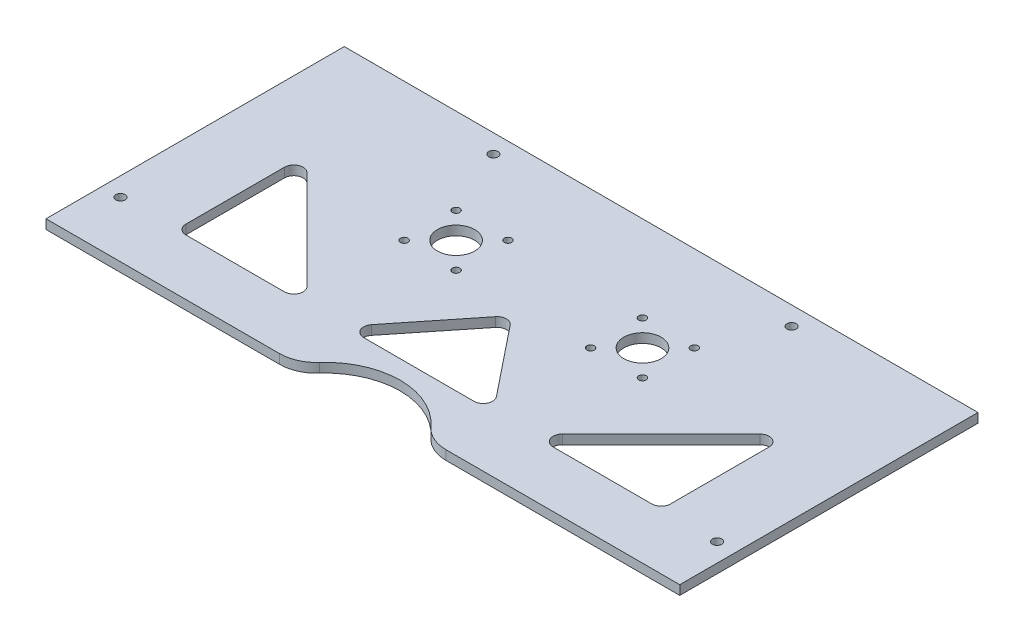
SolidWorks part; units mm, degrees
material "6061-T6 (SS)"
ref_plane "Front Plane" through (0, 0, 0) normal (0, 0, 1) x (1, 0, 0)
ref_plane "Top Plane" through (0, 0, 0) normal (0, 1, 0) x (1, 0, 0)
ref_plane "Right Plane" through (0, 0, 0) normal (1, 0, 0) x (0, 0, -1)
sketch "Sketch1" plane through (0, 0, 0) normal (0, 1, 0) x (1, 0, 0)
  line L0 (0, 101.6) -> (0, 0)
  line L1 (0, 0) -> (215.9, 0)
  line L2 (0, 0) -> (0, 228.6)
  line L3 (0, 228.6) -> (215.9, 228.6)
  line L4 (215.9, 0) -> (215.9, 228.6)
  line L5 (0, 127) -> (85.953, 127)
  line L6 (0, 127) -> (0, 101.6)
  line L7 (0, 101.6) -> (85.953, 101.6)
  line L8 (85.953, 127) -> (85.953, 101.6)
  line L9 (215.9, 127) -> (129.947, 127)
  line L10 (215.9, 127) -> (215.9, 101.6)
  line L11 (215.9, 101.6) -> (129.947, 101.6)
  line L12 (129.947, 127) -> (129.947, 101.6)
  line L13 (215.9, 0) -> (215.9, 101.6)
  circle A0 centre (107.95, 114.3) radius 25.4
  point P13 (85.953, 114.3)
  point P18 (0, 114.3)
  dimension "D4" = 50.8
  dimension "D5" = 85.953
  dimension "D1" = 228.6
  dimension "D2" = 215.9
  dimension "D3" = 25.4
extrude "Boss-Extrude1" add sketch "Sketch1" along normal blind 3.175 contours A0 L9 L4 L3 L2 L5
sketch "Sketch2" plane through (0, 3.175, 0) normal (0, 1, 0) x (1, 0, 0)
  line L0 (0, 190.5) -> (76.2, 190.5) construction
  line L2 (76.2, 190.5) -> (139.7, 190.5) construction
  line L3 (0, 228.6) -> (215.9, 228.6) construction
  line L4 (215.9, 127) -> (215.9, 228.6) construction
  line L5 (139.7, 190.5) -> (215.9, 190.5) construction
  line L8 (0, 127) -> (0, 228.6) construction
  circle A0 centre (76.2, 190.5) radius 6.35
  circle A1 centre (139.7, 190.5) radius 6.35
  dimension "D1" = 12.7
  dimension "D2" = 38.1
  dimension "D3" = 63.5
extrude "Cut-Extrude1" cut sketch "Sketch2" against normal through all
fillet "Fillet1" radius 12.7 2 edges at (129.947, 1.5875, -127) (85.953, 1.5875, -127)
sketch "Sketch3" plane through (0, 3.175, 0) normal (0, 1, 0) x (1, 0, 0)
  line L1 (67.3612, 181.6612) -> (85.0388, 181.6612) construction
  line L2 (67.3612, 181.6612) -> (67.3612, 199.3388) construction
  line L3 (67.3612, 199.3388) -> (85.0388, 199.3388) construction
  line L4 (85.0388, 181.6612) -> (85.0388, 199.3388) construction
  line L5 (67.3612, 181.6612) -> (85.0388, 199.3388) construction
  line L6 (67.3612, 199.3388) -> (85.0388, 181.6612) construction
  line L7 (130.8612, 181.6612) -> (148.5388, 181.6612) construction
  line L8 (130.8612, 181.6612) -> (130.8612, 199.3388) construction
  line L9 (130.8612, 199.3388) -> (148.5388, 199.3388) construction
  line L10 (148.5388, 181.6612) -> (148.5388, 199.3388) construction
  line L11 (130.8612, 181.6612) -> (148.5388, 199.3388) construction
  line L12 (130.8612, 199.3388) -> (148.5388, 181.6612) construction
  circle A0 centre (85.0388, 199.3388) radius 1.27
  circle A1 centre (67.3612, 181.6612) radius 1.27
  circle A2 centre (67.3612, 199.3388) radius 1.27
  circle A3 centre (85.0388, 181.6612) radius 1.27
  circle A4 centre (130.8612, 181.6612) radius 1.27
  circle A5 centre (148.5388, 181.6612) radius 1.27
  circle A6 centre (148.5388, 199.3388) radius 1.27
  circle A7 centre (130.8612, 199.3388) radius 1.27
  point P0 (76.2, 190.5)
  point P6 (139.7, 190.5)
  dimension "D2" = 2.54
  dimension "D1" = 25
extrude "Cut-Extrude2" cut sketch "Sketch3" against normal through all
sketch "Sketch4" plane through (0, 3.175, 0) normal (0, 1, 0) x (1, 0, 0)
  line L0 (0, 127) -> (0, 228.6) construction
  line L1 (0, 127) -> (79.5519, 127) construction
  line L2 (215.9, 127) -> (136.3481, 127) construction
  line L3 (215.9, 127) -> (215.9, 228.6) construction
  line L4 (0, 228.6) -> (215.9, 228.6) construction
  circle A0 centre (6.35, 146.05) radius 1.5875
  circle A1 centre (57.15, 222.25) radius 1.5875
  circle A2 centre (158.75, 222.25) radius 1.5875
  circle A3 centre (209.55, 146.05) radius 1.5875
  dimension "D1" = 3.175
  dimension "D2" = 6.35
  dimension "D3" = 19.05
  dimension "D4" = 19.05
  dimension "D5" = 6.35
  dimension "D6" = 57.15
  dimension "D7" = 6.35
  dimension "D8" = 6.35
  dimension "D9" = 57.15
extrude "Cut-Extrude3" cut sketch "Sketch4" against normal through all
sketch "Sketch5" plane through (0, 3.175, 0) normal (0, 1, 0) x (1, 0, 0)
  line L0 (25.4, 190.5) -> (25.4, 146.05)
  line L1 (25.4, 146.05) -> (69.85, 146.05)
  line L2 (69.85, 146.05) -> (25.4, 190.5)
  line L3 (107.95, 139.7) -> (107.95, 228.6) construction
  line L4 (0, 228.6) -> (215.9, 228.6) construction
  line L5 (0, 127) -> (0, 228.6) construction
  line L6 (0, 127) -> (79.5519, 127) construction
  line L7 (190.5, 146.05) -> (146.05, 146.05)
  line L8 (190.5, 190.5) -> (190.5, 146.05)
  line L9 (146.05, 146.05) -> (190.5, 190.5)
  arc A0 (126.882, 131.2333) -> (89.018, 131.2333) centre (107.95, 114.3) ccw construction
  dimension "D1" = 25.4
  dimension "D2" = 38.1
  dimension "D3" = 38.1
  dimension "D4" = 19.05
extrude "Cut-Extrude4" cut sketch "Sketch5" against normal through all
sketch "Sketch6" plane through (0, 3.175, 0) normal (0, 1, 0) x (1, 0, 0)
  line L0 (82.55, 146.05) -> (133.35, 146.05)
  line L1 (133.35, 146.05) -> (107.95, 177.8)
  line L2 (107.95, 177.8) -> (82.55, 146.05)
  arc A0 (126.882, 131.2333) -> (89.018, 131.2333) centre (107.95, 114.3) ccw construction
  point P3 (107.95, 146.05)
  point P8 (107.95, 139.7)
  dimension "D1" = 6.35
  dimension "D2" = 50.8
  dimension "D3" = 31.75
extrude "Cut-Extrude5" cut sketch "Sketch6" against normal through all
fillet "Fillet2" radius 3.175 9 edges at (69.85, 1.5875, -146.05) (25.4, 1.5875, -146.05) (146.05, 1.5875, -146.05) (190.5, 1.5875, -146.05) (190.5, 1.5875, -190.5) (25.4, 1.5875, -190.5) (133.35, 1.5875, -146.05) (82.55, 1.5875, -146.05) (107.95, 1.5875, -177.8)
